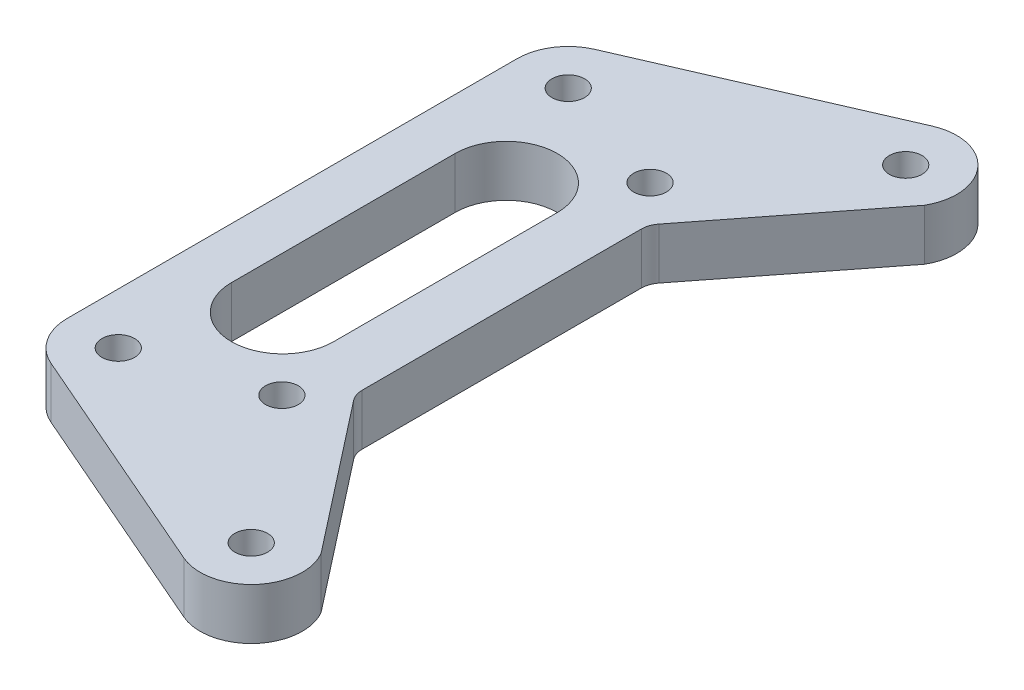
SolidWorks part; units mm, degrees
ref_plane "Ebene vorne" through (0, 0, 0) normal (0, 0, 1) x (1, 0, 0)
ref_plane "Ebene oben" through (0, 0, 0) normal (0, 1, 0) x (1, 0, 0)
ref_plane "Ebene rechts" through (0, 0, 0) normal (1, 0, 0) x (0, 0, -1)
sketch "Skizze1" plane through (0, 0, 0) normal (0, 1, 0) x (1, 0, 0)
  line L0 (49.754, 0) -> (-62.5004, 0) construction
  line L1 (-11.4076, 26.5854) -> (11.5924, 36.5854)
  line L2 (6.5261, 14.9217) -> (17.9178, 29.5028)
  line L3 (-14.414, 22) -> (-14.414, -22)
  line L4 (6.0871, 13.6467) -> (6.0871, -13.6467)
  line L5 (6.5261, -14.9217) -> (17.9178, -29.5028)
  line L6 (-11.4076, -26.5854) -> (11.5924, -36.5854)
  line L7 (-9.414, 10.9357) -> (-9.414, -10.9357)
  line L8 (0.586, 10.9357) -> (0.586, -10.9357)
  circle A0 centre (-9.414, 22) radius 1.6
  circle A1 centre (13.586, 32) radius 1.6
  circle A2 centre (2.586, 18) radius 1.6
  arc A3 (-11.4076, 26.5854) -> (-14.414, 22) centre (-9.414, 22) ccw
  arc A4 (17.9178, 29.5028) -> (11.5924, 36.5854) centre (13.586, 32) ccw
  arc A5 (6.5261, -14.9217) -> (6.0871, -13.6467) centre (8.1582, -13.6467) cw
  arc A6 (6.5261, 14.9217) -> (6.0871, 13.6467) centre (8.1582, 13.6467) ccw
  arc A7 (17.9178, -29.5028) -> (11.5924, -36.5854) centre (13.586, -32) cw
  arc A8 (-11.4076, -26.5854) -> (-14.414, -22) centre (-9.414, -22) cw
  circle A9 centre (2.586, -18) radius 1.6
  circle A10 centre (13.586, -32) radius 1.6
  circle A11 centre (-9.414, -22) radius 1.6
  arc A12 (0.586, 10.9357) -> (-9.414, 10.9357) centre (-4.414, 10.9357) ccw
  arc A13 (0.586, -10.9357) -> (-9.414, -10.9357) centre (-4.414, -10.9357) cw
  point P18 (-14.414, 0)
  point P30 (6.0871, 0)
  point P35 (0.586, 0)
  point P38 (-9.414, 0)
  dimension "D1" = 3.2
  dimension "D2" = 3.2
  dimension "D4" = 3.2
  dimension "D9" = 10
  dimension "D8" = 32
  dimension "D11" = 10
  dimension "D10" = 10
  dimension "D3" = 23
  dimension "D5" = 12
  dimension "D6" = 4
  dimension "D7" = 10
extrude "Aufsatz-Linear austragen1" add sketch "Skizze1" along normal blind 5
sketch "Skizze2" plane through (0, 0, 0) normal (0, -1, 0) x (1, 0, 0)
  circle A0 centre (2.586, -18) radius 3
  circle A1 centre (2.586, 18) radius 3
  dimension "D1" = 6
  dimension "D2" = 6
extrude "Schnitt-Linear austragen1" cut sketch "Skizze2" against normal blind 2.5
